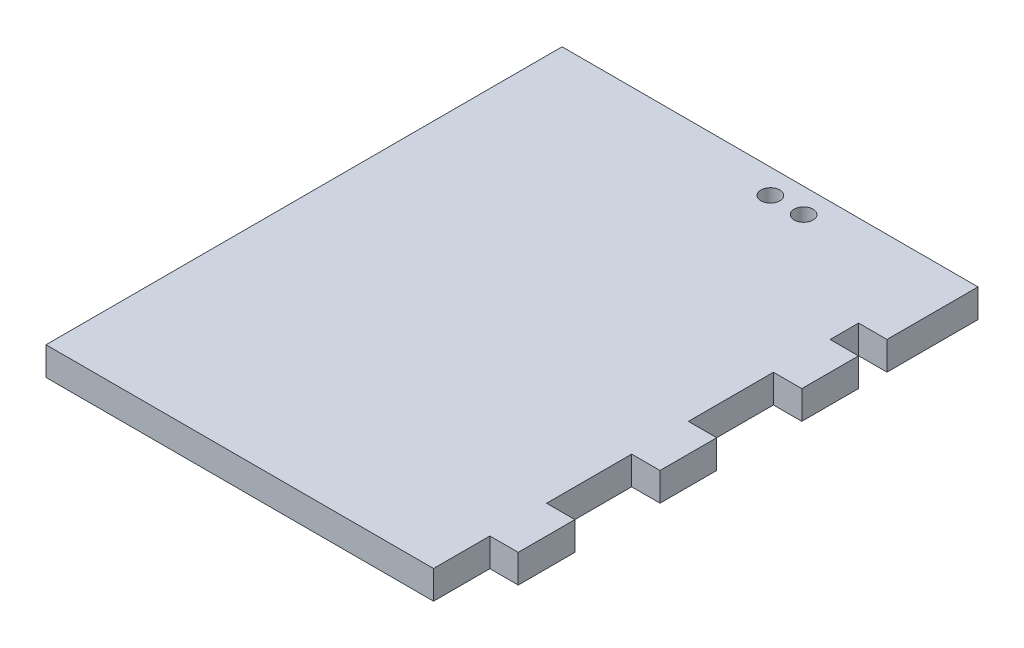
SolidWorks part; units mm, degrees
ref_plane "Front Plane" through (0, 0, 0) normal (0, 0, 1) x (1, 0, 0)
ref_plane "Top Plane" through (0, 0, 0) normal (0, 1, 0) x (1, 0, 0)
ref_plane "Right Plane" through (0, 0, 0) normal (1, 0, 0) x (0, 0, -1)
sketch "Sketch1" plane through (0, 0, 0) normal (0, 1, 0) x (1, 0, 0)
  line L1 (-22, 27.3) -> (22, 27.3)
  line L2 (-22, 27.3) -> (-22, -27.3)
  line L3 (-22, -27.3) -> (22, -27.3)
  line L4 (22, 27.3) -> (22, -27.3)
  line L5 (-22, 27.3) -> (22, -27.3) construction
  line L6 (-22, -27.3) -> (22, 27.3) construction
  circle A0 centre (2.637, 24.7) radius 1
  circle A1 centre (6.15, 24.7) radius 1
  point P0 (0, 0)
  dimension "D1" = 54.6
  dimension "D2" = 44
extrude "Boss-Extrude1" add sketch "Sketch1" along normal blind 3
sketch "Sketch2" plane through (0, 0, 0) normal (0, -1, 0) x (1, 0, 0)
  line L0 (22, -14.6589) -> (19, -14.6589)
  line L1 (22, 27.3) -> (22, -27.3) construction
  line L2 (19, -14.6589) -> (22, -14.6589) construction
  line L3 (19, -49.6829) -> (19, 44.4731) construction
  line L5 (19, -8.6589) -> (22, -8.6589)
  line L6 (22, -8.6589) -> (22, 0.3411)
  line L7 (19, 0.3411) -> (22, 0.3411) construction
  line L8 (22, 0.3411) -> (19, 0.3411)
  line L10 (19, 6.3411) -> (22, 6.3411)
  line L11 (22, 6.3411) -> (19, 6.3411) construction
  line L12 (22, 6.3411) -> (22, 15.3411)
  line L13 (19, 15.3411) -> (22, 15.3411) construction
  line L14 (22, 15.3411) -> (19, 15.3411)
  line L16 (19, 21.3411) -> (22, 21.3411)
  line L17 (22, 21.3411) -> (19, 21.3411) construction
  line L18 (22, 21.3411) -> (22, 27.3)
  line L23 (19, -8.6589) -> (19, 0.3411)
  line L24 (19, 6.3411) -> (19, 15.3411)
  line L25 (19, 21.3411) -> (19, 27.3)
  line L26 (-22, 27.3) -> (22, 27.3) construction
  line L27 (19, 21.3411) -> (19, 27.3411) construction
  line L28 (19, 27.3) -> (22, 27.3)
  line L29 (22, -14.6589) -> (22, -17.6703)
  line L30 (22, -17.6703) -> (19, -17.6703)
  line L31 (19, -17.6703) -> (19, -14.6589)
extrude "Cut-Extrude2" cut sketch "Sketch2" against normal blind 10
sketch "Sketch3" plane through (0, 0, 0) normal (0, -1, 0) x (1, 0, 0)
  line L0 (22, -27.3) -> (-22, -27.3) construction
  line L1 (-22, -27.3) -> (-22, 27.3) construction
  circle A0 centre (6.2, -24.7) radius 1
  circle A1 centre (2.6, -24.7) radius 1
  dimension "D2" = 2
  dimension "D3" = 2
  dimension "D1" = 2.6
  dimension "D4" = 24.6
  dimension "D5" = 28.2
